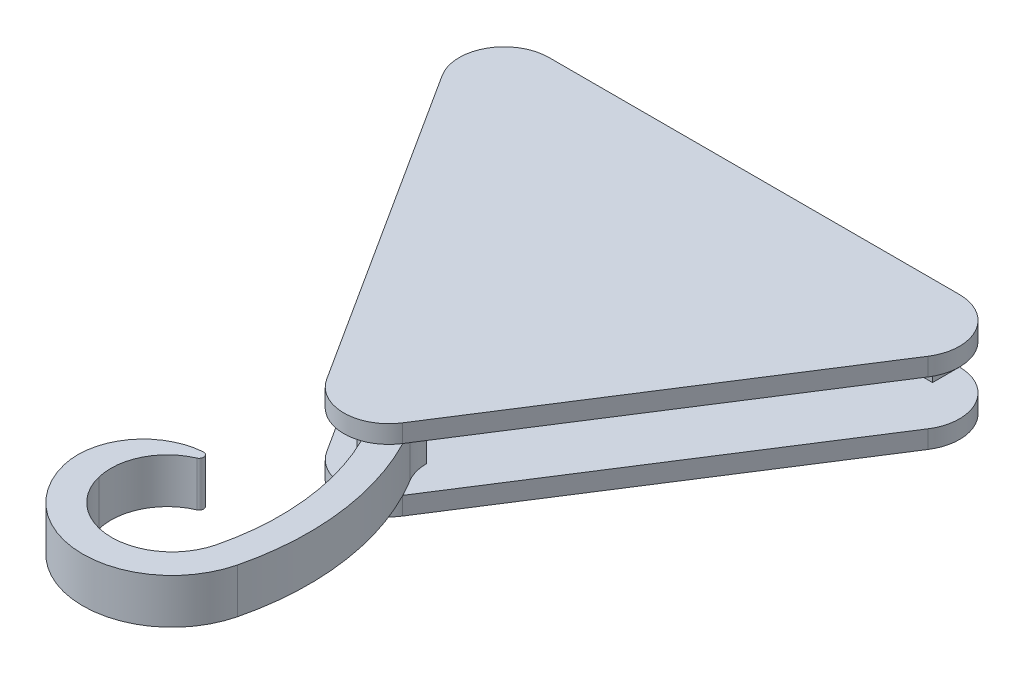
SolidWorks part; units mm, degrees
ref_plane "Front Plane" through (0, 0, 0) normal (0, 0, 1) x (1, 0, 0)
ref_plane "Top Plane" through (0, 0, 0) normal (0, 1, 0) x (1, 0, 0)
ref_plane "Right Plane" through (0, 0, 0) normal (1, 0, 0) x (0, 0, -1)
sketch "Sketch1" plane through (0, 0, 0) normal (0, 1, 0) x (1, 0, 0)
  line L0 (-228.6367, 0) -> (228.6367, 0)
  line L1 (270.7503, -76.9527) -> (42.1136, -434.1975)
  line L2 (0, -49.5) -> (0, 49.5) construction
  line L3 (-270.7503, -76.9527) -> (-42.1136, -434.1975)
  arc A0 (42.1136, -434.1975) -> (-42.1136, -434.1975) centre (0, -407.2449) cw
  arc A1 (270.7503, -76.9527) -> (228.6367, 0) centre (228.6367, -50) ccw
  arc A2 (-270.7503, -76.9527) -> (-228.6367, 0) centre (-228.6367, -50) cw
  point P3 (0, 0)
  point P8 (0, 0)
  point P10 (0, -500)
  point P13 (320, 0)
  point P16 (-320, 0)
  dimension "D3" = 50
  dimension "D1" = 320
  dimension "D2" = 500
extrude "Boss-Extrude1" add sketch "Sketch1" along normal blind 20
sketch "Sketch2" plane through (0, 20, 0) normal (0, 1, 0) x (1, 0, 0)
  line L0 (25, -407.2449) -> (25, -389.9843)
  line L1 (4.2907, -431.8739) -> (4.2907, -431.8739) construction
  line L2 (4.2907, -431.8739) -> (4.2907, -418.4092)
  line L3 (25, -407.2449) -> (25, -404.5851) construction
  arc A0 (25, -407.2449) -> (4.2907, -431.8739) centre (0, -407.2449) ccw
  arc A1 (32.2844, -415.9723) -> (67.471, -642.8879) centre (-224.0093, -571.9003) cw
  arc A2 (67.471, -642.8879) -> (-125.8688, -642.8879) centre (-29.1989, -619.3447) cw
  arc A3 (-125.8688, -642.8879) -> (-60.7341, -553.0278) centre (-55.0952, -625.6515) cw
  arc A4 (10.5082, -442.5566) -> (36.2062, -635.2736) centre (-224.0093, -571.9003) cw
  arc A5 (36.2062, -635.2736) -> (-94.604, -635.2736) centre (-29.1989, -619.3447) cw
  arc A6 (-94.604, -635.2736) -> (-58.3687, -562.6048) centre (-33.4751, -620.3862) cw
  arc A7 (-94.604, -635.2736) -> (-41.8334, -587.2113) centre (-55.0952, -625.6515) cw construction
  arc A8 (-125.8688, -642.8879) -> (-31.3388, -556.792) centre (-55.0952, -625.6515) cw construction
  arc A9 (-58.3687, -562.6048) -> (-60.7341, -553.0278) centre (-60.347, -558.0128) ccw
  arc A10 (4.2907, -431.8739) -> (36.2062, -635.2736) centre (-224.0093, -571.9003) cw construction
  arc A11 (4.2907, -418.4092) -> (10.5082, -442.5566) centre (54.2907, -418.4092) ccw
  arc A12 (25, -404.5851) -> (67.471, -642.8879) centre (-224.0093, -571.9003) cw construction
  arc A13 (32.2844, -415.9723) -> (25, -389.9843) centre (75, -389.9843) cw
  point P23 (0, 0)
  point P24 (0, 0)
  dimension "D1" = 50
  dimension "D2" = 300
  dimension "D4" = 5
  dimension "D5" = 50
extrude "Boss-Extrude2" add sketch "Sketch2" along normal blind 50
pattern_linear "LPattern1" count 2 spacing 70 along (0, 1, 0) of "Boss-Extrude1"
sketch "Sketch3" plane through (0, 20, 0) normal (0, 1, 0) x (1, 0, 0)
  line L1 (228.6367, 0) -> (-228.6367, 0)
  line L2 (228.6367, 0) -> (228.6367, -30)
  line L3 (228.6367, -30) -> (-228.6367, -30)
  line L4 (-228.6367, 0) -> (-228.6367, -30)
  point P5 (0, 0)
  dimension "D1" = 30
extrude "Boss-Extrude3" add sketch "Sketch3" along normal up to next
